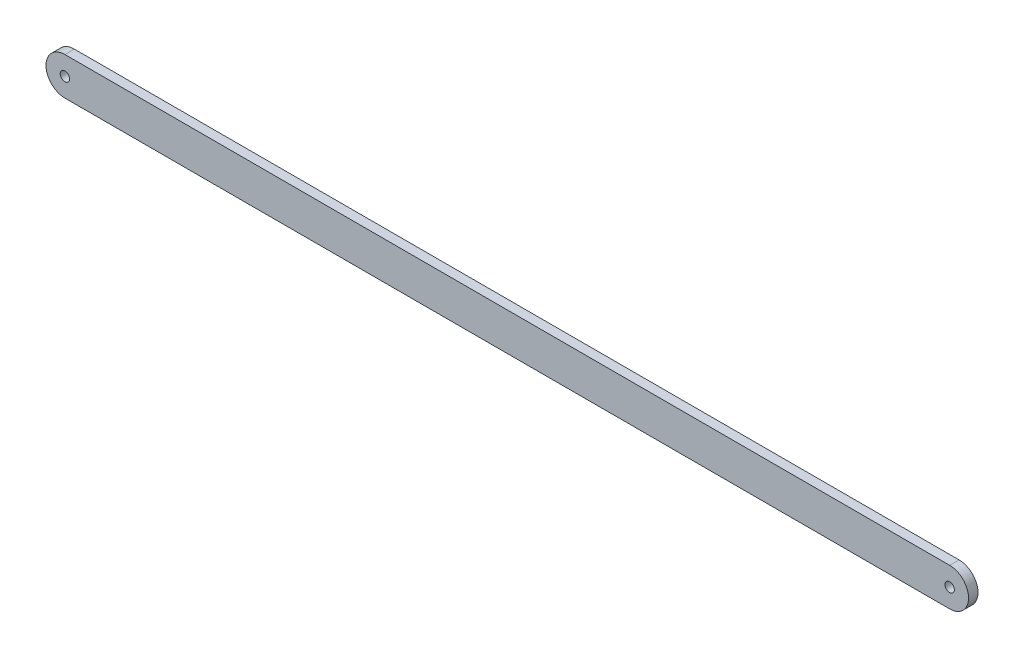
SolidWorks part; units mm, degrees
ref_plane "Front Plane" through (0, 0, 0) normal (0, 0, 1) x (1, 0, 0)
ref_plane "Top Plane" through (0, 0, 0) normal (0, 1, 0) x (1, 0, 0)
ref_plane "Right Plane" through (0, 0, 0) normal (1, 0, 0) x (0, 0, -1)
sketch "Sketch1" plane through (0, 0, 0) normal (0, 0, 1) x (1, 0, 0)
  line L0 (-150, 6.4) -> (150, 6.4)
  line L1 (-150, -6.4) -> (150, -6.4)
  line L2 (0, 6.4) -> (0, -6.4) construction
  circle A0 centre (-150, 0) radius 1.5875
  circle A1 centre (150, 0) radius 1.5875
  arc A2 (-150, 6.4) -> (-150, -6.4) centre (-150, 0) ccw
  arc A3 (150, -6.4) -> (150, 6.4) centre (150, 0) ccw
extrude "Boss-Extrude2" add sketch "Sketch1" along normal mid plane 3.2
